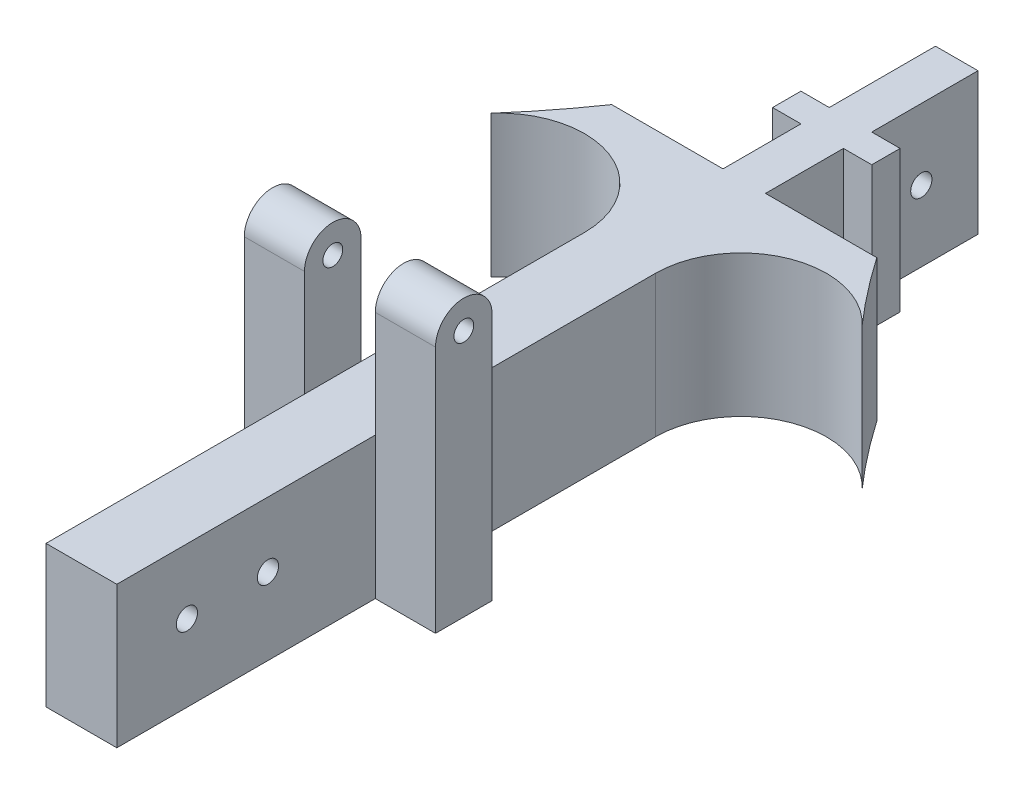
SolidWorks part; units mm, degrees
ref_plane "Plan de face" through (0, 0, 0) normal (0, 0, 1) x (1, 0, 0)
ref_plane "Plan de dessus" through (0, 0, 0) normal (0, 1, 0) x (1, 0, 0)
ref_plane "Plan de droite" through (0, 0, 0) normal (1, 0, 0) x (0, 0, -1)
sketch "Esquisse1" plane through (0, 0, 0) normal (0, 1, 0) x (1, 0, 0)
  line L0 (-3, 84.3983) -> (-3, 69.3983)
  line L1 (-3, 84.3983) -> (0, 84.3983)
  line L2 (-3, 65.3983) -> (-3, 54.3983)
  line L3 (-5, -39.1827) -> (0, -39.1827)
  line L4 (0, 84.3983) -> (0, -39.1827)
  line L5 (-3, 69.3983) -> (-7, 69.3983)
  line L6 (-3, 54.3983) -> (-18.71, 54.3983)
  line L7 (-3, 65.3983) -> (-7, 65.3983)
  line L8 (-7, 69.3983) -> (-7, 65.3983)
  line L9 (-5, 36.8425) -> (-5, -39.1827)
  arc A0 (-26.1833, 44.8157) -> (-18.71, 54.3983) centre (-105.5, 114.3795) ccw
  arc A1 (-5, 36.8425) -> (-26.1833, 44.8157) centre (-17.0922, 36.8425) ccw
  dimension "D7" = 211
  dimension "D1" = 3
  dimension "D2" = 4
  dimension "D3" = 4
  dimension "D4" = 15
  dimension "D5" = 11
  dimension "D6" = 15.71
extrude "Boss.-Extru.1" add sketch "Esquisse1" along normal blind 20
mirror "Symétrie1" about plane through (0, 20, -84.3983) normal (-1, 0, 0) of "Boss.-Extru.1"
sketch "Esquisse3" plane through (-3, 0, 0) normal (-1, 0, 0) x (0, 0, 1)
  line L2 (-84.3983, 20) -> (-69.3983, 20) construction
  line L3 (-65.3983, 20) -> (-54.3983, 20) construction
  line L4 (-84.3983, 20) -> (-84.3983, 0) construction
  circle A0 centre (-76.3983, 10) radius 1.5
  circle A1 centre (-60.3983, 10) radius 1.5
  dimension "D1" = 3
  dimension "D2" = 3
  dimension "D3" = 10
  dimension "D4" = 10
  dimension "D5" = 8
  dimension "D6" = 24
extrude "Enlèv. mat.-Extru.3" cut sketch "Esquisse3" against normal blind 20
sketch "Esquisse4" plane through (-5, 0, 0) normal (-1, 0, 0) x (0, 0, 1)
  circle A0 centre (29.292, 10.84) radius 1.5
extrude "Enlèv. mat.-Extru.4" cut sketch "Esquisse4" against normal blind 10
sketch "Esquisse5" plane through (-5, 0, 0) normal (-1, 0, 0) x (0, 0, 1)
  circle A0 centre (17.842, 10.84) radius 1.5
extrude "Enlèv. mat.-Extru.5" cut sketch "Esquisse5" against normal blind 10
sketch "Esquisse6" plane through (5, 0, 0) normal (1, 0, 0) x (0, 0, -1)
  line L0 (36.8425, 0) -> (-39.1827, 0) construction
  line L1 (5.3082, 0) -> (-2.6918, 0)
  line L2 (5.3082, 0) -> (5.3082, 35)
  line L4 (-2.6918, 0) -> (-2.6918, 35)
  arc A0 (-2.6918, 35) -> (5.3082, 35) centre (1.3082, 35) cw
  circle A1 centre (1.3082, 35) radius 1.4
  dimension "D2" = 35
  dimension "D1" = 8
ref_plane "Plan1" through (0, 0, 0) normal (-1, 0, 0) x (0, 0, 1)
extrude "Boss.-Extru.2" add sketch "Esquisse6" along normal blind 8.5
mirror "Symétrie2" about plane through (0, 0, 0) normal (-1, 0, 0) of "Boss.-Extru.2"
